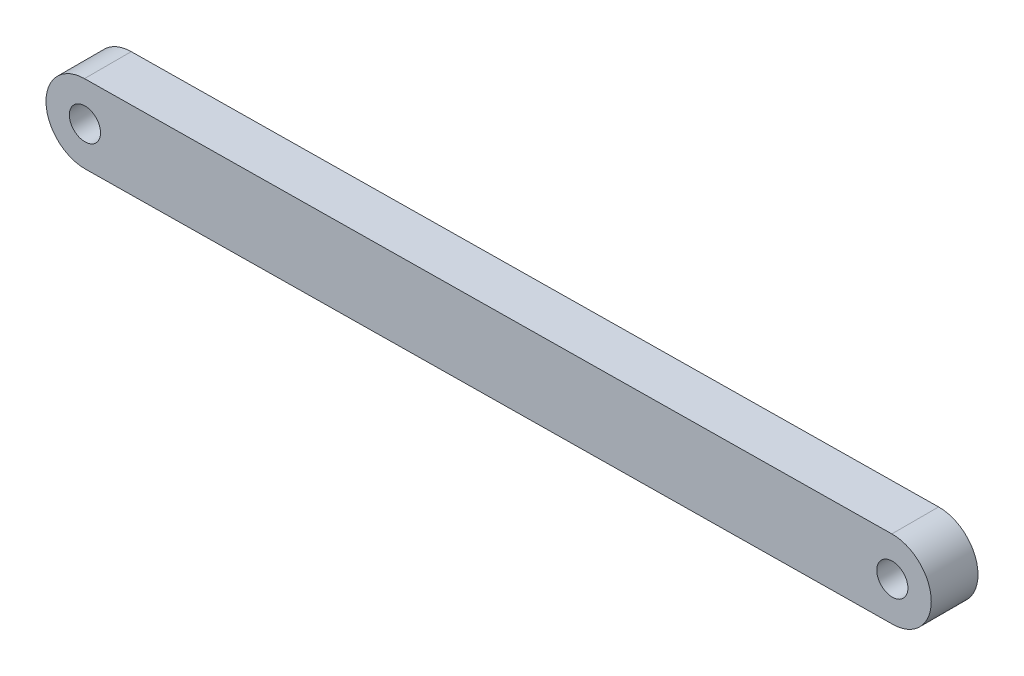
SolidWorks part; units mm, degrees
ref_plane "Front Plane" through (0, 0, 0) normal (0, 0, 1) x (1, 0, 0)
ref_plane "Top Plane" through (0, 0, 0) normal (0, 1, 0) x (1, 0, 0)
ref_plane "Right Plane" through (0, 0, 0) normal (1, 0, 0) x (0, 0, -1)
sketch "Sketch1" plane through (0, 0, 0) normal (0, 0, 1) x (1, 0, 0)
  line L0 (-20.227, -0.6026) -> (31.593, 0) construction
  line L1 (-20.256, 1.8972) -> (31.564, 2.4998)
  line L2 (-20.1979, -3.1025) -> (31.6221, -2.4998)
  arc A0 (-20.256, 1.8972) -> (-20.1979, -3.1025) centre (-20.227, -0.6026) ccw
  arc A1 (31.6221, -2.4998) -> (31.564, 2.4998) centre (31.593, 0) ccw
  point P2 (5.683, -0.3013)
  dimension "D1" = 51.82
  dimension "D2" = 5
extrude "Boss-Extrude1" add sketch "Sketch1" along normal blind 3
sketch "Sketch2" plane through (0, 0, 3) normal (0, 0, 1) x (1, 0, 0)
  circle A0 centre (31.593, 0) radius 1
  circle A1 centre (-20.227, -0.6026) radius 1
  dimension "D1" = 2
  dimension "D2" = 2
extrude "Cut-Extrude1" cut sketch "Sketch2" against normal through all
